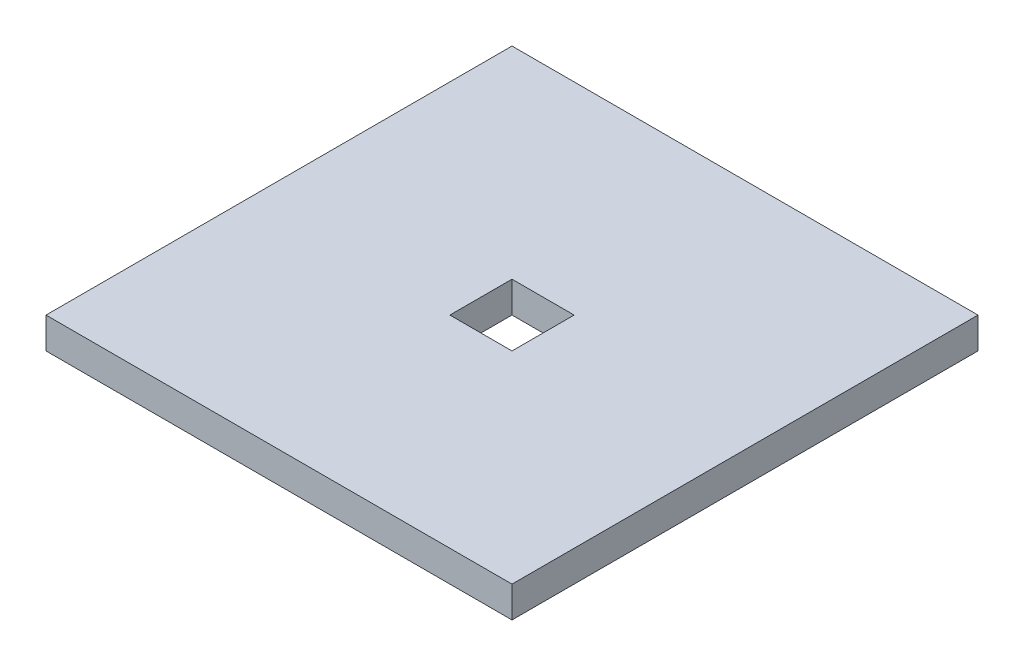
SolidWorks part; units mm, degrees
ref_plane "前视基准面" through (0, 0, 0) normal (0, 0, 1) x (1, 0, 0)
ref_plane "上视基准面" through (0, 0, 0) normal (0, 1, 0) x (1, 0, 0)
ref_plane "右视基准面" through (0, 0, 0) normal (1, 0, 0) x (0, 0, -1)
sketch "Sketch1" plane through (0, 0, 0) normal (0, 1, 0) x (1, 0, 0)
  line L1 (0, 0) -> (1500, 0)
  line L2 (0, 0) -> (0, 1500)
  line L3 (0, 1500) -> (1500, 1500)
  line L4 (1500, 0) -> (1500, 1500)
  line L5 (650, 850) -> (850, 850)
  line L6 (650, 850) -> (650, 650)
  line L7 (650, 650) -> (850, 650)
  line L8 (850, 850) -> (850, 650)
  dimension "D1" = 1500
  dimension "D2" = 1500
  dimension "D3" = 200
  dimension "D4" = 200
  dimension "D5" = 650
  dimension "D6" = 650
extrude "Boss-Extrude1" add sketch "Sketch1" along normal blind 100 contours L1 L4 L3 L2 L5 L8 L7 L6
